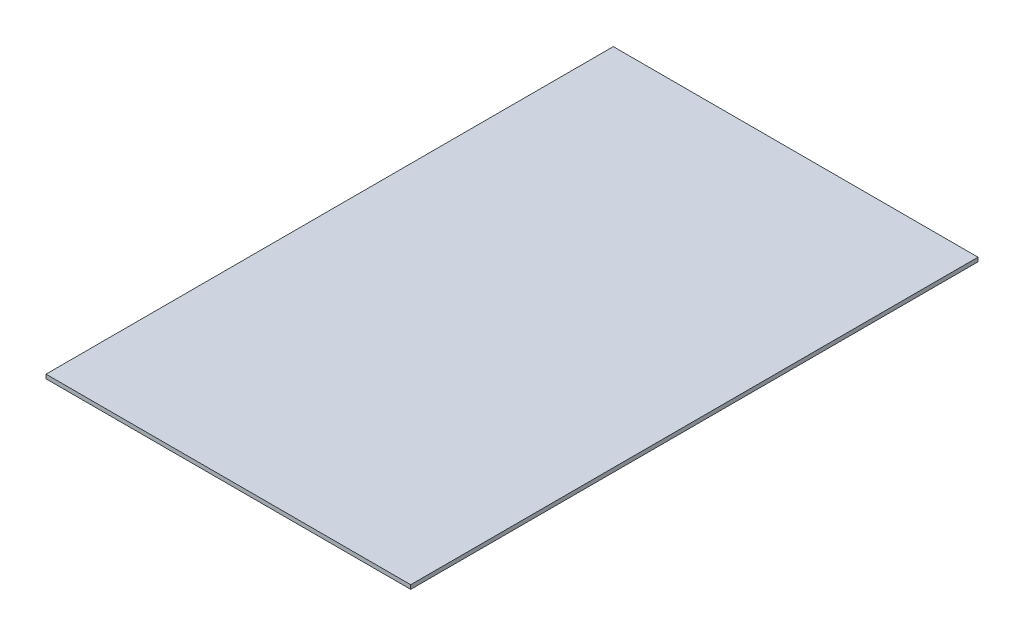
SolidWorks part; units mm, degrees
ref_plane "前视基准面" through (0, 0, 0) normal (0, 0, 1) x (1, 0, 0)
ref_plane "上视基准面" through (0, 0, 0) normal (0, 1, 0) x (1, 0, 0)
ref_plane "右视基准面" through (0, 0, 0) normal (1, 0, 0) x (0, 0, -1)
other "Configuration Table"
sketch "草图1" plane through (0, 0, 0) normal (0, 1, 0) x (1, 0, 0)
  line L0 (0, 0) -> (180, 0)
  line L1 (180, 0) -> (180, -280)
  line L2 (180, -280) -> (0, -280)
  line L3 (0, -280) -> (0, 0)
extrude "凸台-拉伸1" add sketch "草图1" along normal blind 2
